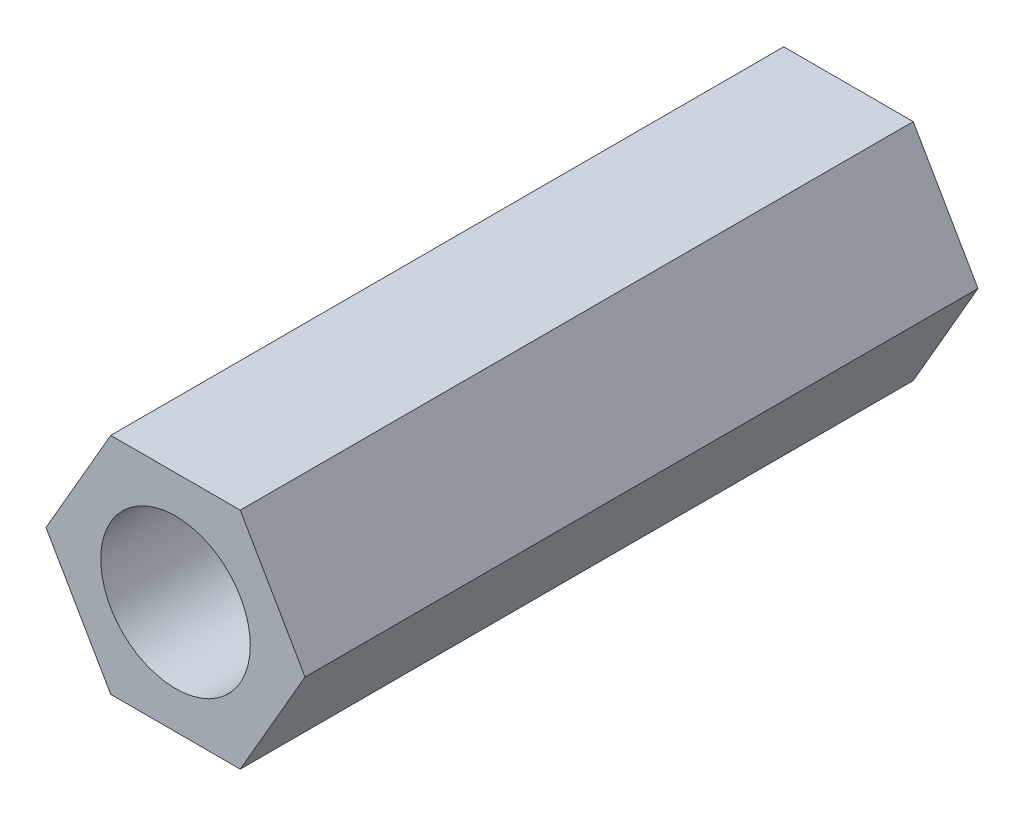
SolidWorks part; units mm, degrees
ref_plane "前视基准面" through (0, 0, 0) normal (0, 0, 1) x (1, 0, 0)
ref_plane "上视基准面" through (0, 0, 0) normal (0, 1, 0) x (1, 0, 0)
ref_plane "右视基准面" through (0, 0, 0) normal (1, 0, 0) x (0, 0, -1)
sketch "草图1" plane through (0, 0, 0) normal (0, 0, 1) x (1, 0, 0)
  line L1 (1.7321, 0) -> (0.866, 1.5)
  line L2 (0.866, 1.5) -> (-0.866, 1.5)
  line L3 (-0.866, 1.5) -> (-1.7321, 0)
  line L4 (-1.7321, 0) -> (-0.866, -1.5)
  line L5 (-0.866, -1.5) -> (0.866, -1.5)
  line L6 (0.866, -1.5) -> (1.7321, 0)
  circle A0 centre (0, 0) radius 1
  circle A1 centre (0, 0) radius 1.5 construction
  dimension "D1" = 2
  dimension "D2" = 3
extrude "凸台-拉伸1" add sketch "草图1" along normal blind 9
